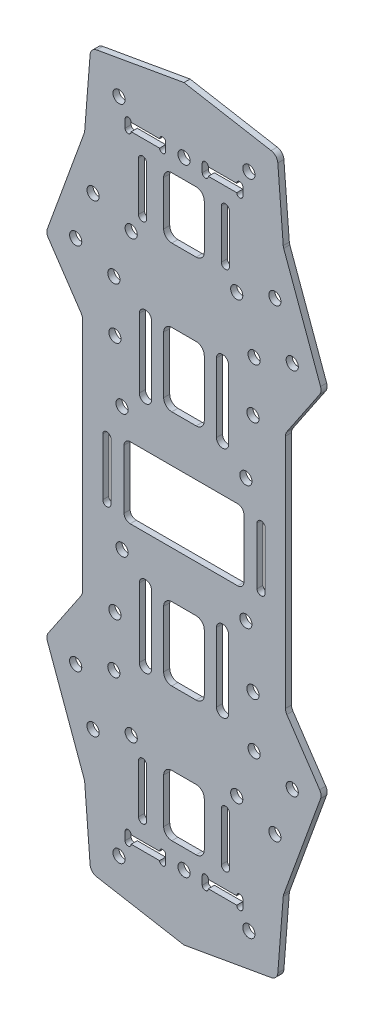
SolidWorks part; units mm, degrees
ref_plane "Alzado" through (0, 0, 0) normal (0, 0, 1) x (1, 0, 0)
ref_plane "Planta" through (0, 0, 0) normal (0, 1, 0) x (1, 0, 0)
ref_plane "Vista lateral" through (0, 0, 0) normal (1, 0, 0) x (0, 0, -1)
ref_plane "Plano1" through (0, 0, 1.5) normal (0, 0, 1) x (1, 0, 0)
sketch "Croquis1" plane through (0, 0, 1.5) normal (0, 0, 1) x (1, 0, 0)
  line L0 (-18, 7) -> (-18, -7)
  line L1 (-20, -7) -> (-20, 7)
  line L2 (9.2, -70.25) -> (9.2, -58.25)
  line L3 (11.2, -58.25) -> (11.2, -70.25)
  line L4 (-11, -37.25) -> (-11, -20.25)
  line L5 (-8, -20.25) -> (-8, -37.25)
  line L6 (-5, -36.25) -> (-5, -22.25)
  line L7 (-3, -20.25) -> (3, -20.25)
  line L8 (5, -22.25) -> (5, -36.25)
  line L9 (3, -38.25) -> (-3, -38.25)
  line L10 (-9.2, 70.25) -> (-9.2, 58.25)
  line L11 (-11.2, 58.25) -> (-11.2, 70.25)
  line L12 (11, 37.25) -> (11, 20.25)
  line L13 (8, 20.25) -> (8, 37.25)
  line L14 (14.75, 7.25) -> (14.75, -7.25)
  line L15 (13.25, -8.75) -> (-13.25, -8.75)
  line L16 (-14.75, -7.25) -> (-14.75, 7.25)
  line L17 (-13.25, 8.75) -> (13.25, 8.75)
  line L18 (-5, 22.25) -> (-5, 36.25)
  line L19 (-3, 38.25) -> (3, 38.25)
  line L20 (5, 36.25) -> (5, 22.25)
  line L21 (3, 20.25) -> (-3, 20.25)
  line L22 (33.6515, 43.9576) -> (24.5714, 68.9048)
  line L23 (24.457, 69.4319) -> (23.1215, 86.4007)
  line L24 (21.475, 88.2134) -> (0, 92)
  line L25 (0, 92) -> (-21.475, 88.2134)
  line L26 (-23.1215, 86.4007) -> (-24.457, 69.4319)
  line L27 (-24.5714, 68.9048) -> (-33.6515, 43.9576)
  line L28 (-33.4302, 42.1552) -> (-25.3419, 30.1639)
  line L29 (-25, 29.0455) -> (-25, -29.0455)
  line L30 (-25.3419, -30.1639) -> (-33.4302, -42.1552)
  line L31 (-33.6515, -43.9576) -> (-24.5714, -68.9048)
  line L32 (-24.457, -69.4319) -> (-23.1215, -86.4007)
  line L33 (-21.475, -88.2134) -> (0, -92)
  line L34 (0, -92) -> (21.475, -88.2134)
  line L35 (23.1215, -86.4007) -> (24.457, -69.4319)
  line L36 (24.5714, -68.9048) -> (33.6515, -43.9576)
  line L37 (33.4302, -42.1552) -> (25.3419, -30.1639)
  line L38 (25, -29.0455) -> (25, 29.0455)
  line L39 (25.3419, 30.1639) -> (33.4302, 42.1552)
  line L40 (-3, 71.25) -> (3, 71.25)
  line L41 (5, 69.25) -> (5, 58.25)
  line L42 (3, 56.25) -> (-3, 56.25)
  line L43 (-5, 58.25) -> (-5, 69.25)
  line L44 (11.2, 70.25) -> (11.2, 58.25)
  line L45 (9.2, 58.25) -> (9.2, 70.25)
  line L46 (-8, 37.25) -> (-8, 20.25)
  line L47 (-11, 20.25) -> (-11, 37.25)
  line L48 (3, -71.25) -> (-3, -71.25)
  line L49 (-5, -69.25) -> (-5, -58.25)
  line L50 (-3, -56.25) -> (3, -56.25)
  line L51 (5, -58.25) -> (5, -69.25)
  line L52 (-11.2, -70.25) -> (-11.2, -58.25)
  line L53 (-9.2, -58.25) -> (-9.2, -70.25)
  line L54 (8, -37.25) -> (8, -20.25)
  line L55 (11, -20.25) -> (11, -37.25)
  line L56 (20, 7) -> (20, -7)
  line L57 (18, -7) -> (18, 7)
  line L58 (14.5, 77) -> (14.5, 75)
  line L59 (13, 75) -> (6, 75)
  line L60 (4.5, 75) -> (4.5, 77)
  line L61 (6, 77) -> (13, 77)
  line L62 (-13, 77) -> (-6, 77)
  line L63 (-4.5, 77) -> (-4.5, 75)
  line L64 (-6, 75) -> (-13, 75)
  line L65 (-14.5, 75) -> (-14.5, 77)
  line L66 (-6, -77) -> (-13, -77)
  line L67 (-14.5, -77) -> (-14.5, -75)
  line L68 (-13, -75) -> (-6, -75)
  line L69 (-4.5, -75) -> (-4.5, -77)
  line L70 (13, -77) -> (6, -77)
  line L71 (4.5, -77) -> (4.5, -75)
  line L72 (6, -75) -> (13, -75)
  line L73 (14.5, -75) -> (14.5, -77)
  arc A0 (-18, -7) -> (-20, -7) centre (-19, -7) cw
  arc A1 (-20, 7) -> (-18, 7) centre (-19, 7) cw
  arc A2 (9.2, -58.25) -> (11.2, -58.25) centre (10.2, -58.25) cw
  arc A3 (11.2, -70.25) -> (9.2, -70.25) centre (10.2, -70.25) cw
  arc A4 (-11, -20.25) -> (-8, -20.25) centre (-9.5, -20.25) cw
  arc A5 (-8, -37.25) -> (-11, -37.25) centre (-9.5, -37.25) cw
  arc A6 (-5, -22.25) -> (-3, -20.25) centre (-3, -22.25) cw
  arc A7 (3, -20.25) -> (5, -22.25) centre (3, -22.25) cw
  arc A8 (5, -36.25) -> (3, -38.25) centre (3, -36.25) cw
  arc A9 (-3, -38.25) -> (-5, -36.25) centre (-3, -36.25) cw
  arc A10 (-9.2, 58.25) -> (-11.2, 58.25) centre (-10.2, 58.25) cw
  arc A11 (-11.2, 70.25) -> (-9.2, 70.25) centre (-10.2, 70.25) cw
  arc A12 (11, 20.25) -> (8, 20.25) centre (9.5, 20.25) cw
  arc A13 (8, 37.25) -> (11, 37.25) centre (9.5, 37.25) cw
  arc A14 (14.75, -7.25) -> (13.25, -8.75) centre (13.25, -7.25) cw
  arc A15 (-13.25, -8.75) -> (-14.75, -7.25) centre (-13.25, -7.25) cw
  arc A16 (-14.75, 7.25) -> (-13.25, 8.75) centre (-13.25, 7.25) cw
  arc A17 (13.25, 8.75) -> (14.75, 7.25) centre (13.25, 7.25) cw
  arc A18 (-5, 36.25) -> (-3, 38.25) centre (-3, 36.25) cw
  arc A19 (3, 38.25) -> (5, 36.25) centre (3, 36.25) cw
  arc A20 (5, 22.25) -> (3, 20.25) centre (3, 22.25) cw
  arc A21 (-3, 20.25) -> (-5, 22.25) centre (-3, 22.25) cw
  arc A22 (24.5714, 68.9048) -> (24.457, 69.4319) centre (26.4508, 69.5889) cw
  arc A23 (23.1215, 86.4007) -> (21.475, 88.2134) centre (21.1277, 86.2438) ccw
  arc A24 (-21.475, 88.2134) -> (-23.1215, 86.4007) centre (-21.1277, 86.2438) ccw
  arc A25 (-24.457, 69.4319) -> (-24.5714, 68.9048) centre (-26.4508, 69.5889) cw
  arc A26 (-33.6515, 43.9576) -> (-33.4302, 42.1552) centre (-31.7721, 43.2736) ccw
  arc A27 (-25.3419, 30.1639) -> (-25, 29.0455) centre (-27, 29.0455) cw
  arc A28 (-25, -29.0455) -> (-25.3419, -30.1639) centre (-27, -29.0455) cw
  arc A29 (-33.4302, -42.1552) -> (-33.6515, -43.9576) centre (-31.7721, -43.2736) ccw
  arc A30 (-24.5714, -68.9048) -> (-24.457, -69.4319) centre (-26.4508, -69.5889) cw
  arc A31 (-23.1215, -86.4007) -> (-21.475, -88.2134) centre (-21.1277, -86.2438) ccw
  arc A32 (21.475, -88.2134) -> (23.1215, -86.4007) centre (21.1277, -86.2438) ccw
  arc A33 (24.457, -69.4319) -> (24.5714, -68.9048) centre (26.4508, -69.5889) cw
  arc A34 (33.6515, -43.9576) -> (33.4302, -42.1552) centre (31.7721, -43.2736) ccw
  arc A35 (25.3419, -30.1639) -> (25, -29.0455) centre (27, -29.0455) cw
  arc A36 (25, 29.0455) -> (25.3419, 30.1639) centre (27, 29.0455) cw
  arc A37 (33.4302, 42.1552) -> (33.6515, 43.9576) centre (31.7721, 43.2736) ccw
  arc A38 (3, 71.25) -> (5, 69.25) centre (3, 69.25) cw
  arc A39 (5, 58.25) -> (3, 56.25) centre (3, 58.25) cw
  arc A40 (-3, 56.25) -> (-5, 58.25) centre (-3, 58.25) cw
  arc A41 (-5, 69.25) -> (-3, 71.25) centre (-3, 69.25) cw
  arc A42 (11.2, 58.25) -> (9.2, 58.25) centre (10.2, 58.25) cw
  arc A43 (9.2, 70.25) -> (11.2, 70.25) centre (10.2, 70.25) cw
  arc A44 (-8, 20.25) -> (-11, 20.25) centre (-9.5, 20.25) cw
  arc A45 (-11, 37.25) -> (-8, 37.25) centre (-9.5, 37.25) cw
  arc A46 (-3, -71.25) -> (-5, -69.25) centre (-3, -69.25) cw
  arc A47 (-5, -58.25) -> (-3, -56.25) centre (-3, -58.25) cw
  arc A48 (3, -56.25) -> (5, -58.25) centre (3, -58.25) cw
  arc A49 (5, -69.25) -> (3, -71.25) centre (3, -69.25) cw
  arc A50 (-11.2, -58.25) -> (-9.2, -58.25) centre (-10.2, -58.25) cw
  arc A51 (-9.2, -70.25) -> (-11.2, -70.25) centre (-10.2, -70.25) cw
  arc A52 (8, -20.25) -> (11, -20.25) centre (9.5, -20.25) cw
  arc A53 (11, -37.25) -> (8, -37.25) centre (9.5, -37.25) cw
  arc A54 (20, -7) -> (18, -7) centre (19, -7) cw
  arc A55 (18, 7) -> (20, 7) centre (19, 7) cw
  circle A56 centre (16, 81) radius 1.5
  circle A57 centre (0, 76) radius 1.5
  circle A58 centre (26.6722, 45.4202) radius 1.5
  circle A59 centre (22.3969, 57.1664) radius 1.5
  circle A60 centre (17.2753, 42) radius 1.5
  circle A61 centre (13, 53.7462) radius 1.5
  circle A62 centre (17, 29.5) radius 1.5
  circle A63 centre (15.25, 15.25) radius 1.5
  circle A64 centre (-15.25, 15.25) radius 1.5
  circle A65 centre (-17, 29.5) radius 1.5
  circle A66 centre (-13, 53.7462) radius 1.5
  circle A67 centre (-17.2753, 42) radius 1.5
  circle A68 centre (-22.3969, 57.1664) radius 1.5
  circle A69 centre (-26.6722, 45.4202) radius 1.5
  circle A70 centre (-16, 81) radius 1.5
  circle A71 centre (-16, -81) radius 1.5
  circle A72 centre (-26.6722, -45.4202) radius 1.5
  circle A73 centre (-22.3969, -57.1664) radius 1.5
  circle A74 centre (-17.2753, -42) radius 1.5
  circle A75 centre (-13, -53.7462) radius 1.5
  circle A76 centre (-17, -29.5) radius 1.5
  circle A77 centre (-15.25, -15.25) radius 1.5
  circle A78 centre (15.25, -15.25) radius 1.5
  circle A79 centre (17, -29.5) radius 1.5
  circle A80 centre (13, -53.7462) radius 1.5
  circle A81 centre (17.2753, -42) radius 1.5
  circle A82 centre (22.3969, -57.1664) radius 1.5
  circle A83 centre (26.6722, -45.4202) radius 1.5
  circle A84 centre (0, -76) radius 1.5
  circle A85 centre (16, -81) radius 1.5
  arc A86 (13, 77) -> (14.5, 77) centre (13.75, 77) cw
  arc A87 (14.5, 75) -> (13, 75) centre (13.75, 75) cw
  arc A88 (6, 75) -> (4.5, 75) centre (5.25, 75) cw
  arc A89 (4.5, 77) -> (6, 77) centre (5.25, 77) cw
  arc A90 (-14.5, 77) -> (-13, 77) centre (-13.75, 77) cw
  arc A91 (-6, 77) -> (-4.5, 77) centre (-5.25, 77) cw
  arc A92 (-4.5, 75) -> (-6, 75) centre (-5.25, 75) cw
  arc A93 (-13, 75) -> (-14.5, 75) centre (-13.75, 75) cw
  arc A94 (-4.5, -77) -> (-6, -77) centre (-5.25, -77) cw
  arc A95 (-13, -77) -> (-14.5, -77) centre (-13.75, -77) cw
  arc A96 (-14.5, -75) -> (-13, -75) centre (-13.75, -75) cw
  arc A97 (-6, -75) -> (-4.5, -75) centre (-5.25, -75) cw
  arc A98 (14.5, -77) -> (13, -77) centre (13.75, -77) cw
  arc A99 (6, -77) -> (4.5, -77) centre (5.25, -77) cw
  arc A100 (4.5, -75) -> (6, -75) centre (5.25, -75) cw
  arc A101 (13, -75) -> (14.5, -75) centre (13.75, -75) cw
extrude "Saliente-Extruir1" add sketch "Croquis1" against normal blind 1.5
